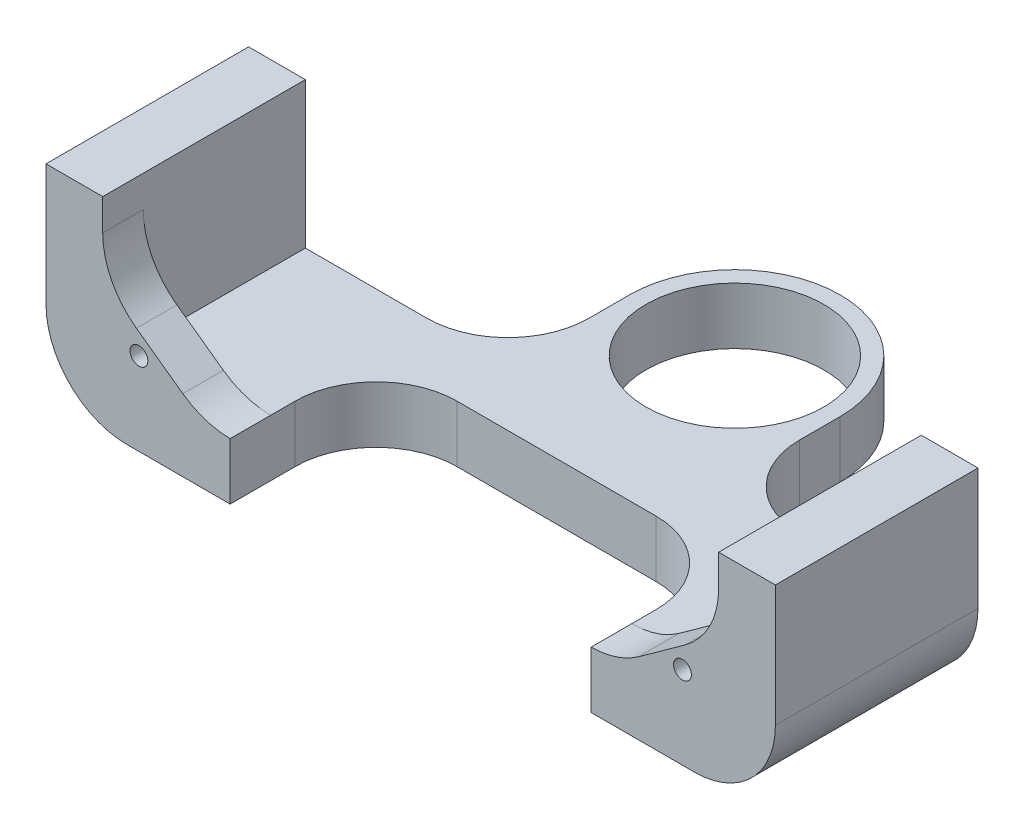
SolidWorks part; units mm, degrees
material "PVC 0.007 Plasticized"
ref_plane "Front Plane" through (0, 0, 0) normal (0, 0, 1) x (1, 0, 0)
ref_plane "Top Plane" through (0, 0, 0) normal (0, 1, 0) x (1, 0, 0)
ref_plane "Right Plane" through (0, 0, 0) normal (1, 0, 0) x (0, 0, -1)
sketch "Sketch1" plane through (0, 0, 0) normal (0, 1, 0) x (1, 0, 0)
  line L2 (0, 0) -> (0, -40)
  line L3 (0, -40) -> (26, -40)
  line L4 (26, 0) -> (26, -40)
  arc A0 (26, 0) -> (0, 0) centre (13, 0) ccw
  circle A1 centre (13, 0) radius 10.975
  dimension "D3" = 21.95
  dimension "D1" = 40
  dimension "D2" = 26
extrude "Boss-Extrude1" add sketch "Sketch1" along normal blind 7
sketch "Sketch2" plane through (0, 0, 40) normal (0, 0, 1) x (1, 0, 0)
  line L0 (26, 0) -> (58, 0)
  line L1 (58, 0) -> (58, 25)
  line L2 (58, 25) -> (51, 25)
  line L3 (51, 25) -> (51, 7) construction
  line L4 (51, 7) -> (26, 7) construction
  line L5 (26, 7) -> (26, 0) construction
  line L6 (0, 0) -> (26, 0) construction
  line L7 (51, 16) -> (38.5, 7)
  line L8 (38.5, 7) -> (26, 7)
  line L9 (51, 16) -> (51, 25)
  line L10 (44.75, 11.5) -> (51, 7) construction
  circle A0 centre (46.5354, 10.2145) radius 1.1
  point P13 (13, 0)
  point P20 (46.6726, 10.1158)
  line M8 (26, 0) -> (26, 7)
  dimension "D3" = 2.2
  dimension "D1" = 45
  dimension "D2" = 25
  dimension "D4" = 2.2
extrude "Boss-Extrude2" add sketch "Sketch2" against normal blind 5 contours L9 L7 L8 L0 L1 L2 A0 M8
sketch "Sketch3" plane through (0, 0, 35) normal (0, 0, -1) x (-1, 0, 0)
  line L0 (-51, 16) -> (-51, 7)
  line L1 (-51, 7) -> (-38.5, 7)
  line L7 (-51, 16) -> (-51, 25)
  line L8 (-51, 25) -> (-58, 25)
  line L9 (-58, 25) -> (-58, 0)
  line L10 (-58, 0) -> (-26, 0)
  line L11 (-26, 0) -> (-26, 7)
  line L12 (-26, 7) -> (-38.5, 7)
  line L13 (-38.5, 7) -> (-51, 16)
  line L14 (-51, 16) -> (-51, 25)
  line L15 (-51, 25) -> (-58, 25)
  line L16 (-58, 25) -> (-58, 0)
  line L17 (-58, 0) -> (-26, 0)
  line L18 (-26, 0) -> (-26, 7)
  line L19 (-26, 7) -> (-38.5, 7)
  dimension "D1" = 0
extrude "Boss-Extrude3" add sketch "Sketch3" along normal blind 20
ref_plane "Plane1" through (13, 0, 0) normal (1, 0, 0) x (0, 0, -1)
mirror "Mirror1" about plane through (13, 0, 0) normal (1, 0, 0) of "Boss-Extrude3", "Boss-Extrude2"
fillet "Fillet1" radius 10 8 edges at (51, 16, 37.5) (58, 0, 27.5) (38.5, 7, 37.5) (26, 3.5, 15) (-25, 16, 37.5) (-12.5, 7, 37.5) (-32, 0, 27.5) (0, 3.5, 15)
sketch "Sketch5" plane through (0, 7, 0) normal (0, 1, 0) x (1, 0, 0)
  line L0 (-9.2745, -35) -> (-9.2745, -40) construction
  line L1 (-9.2745, -22) -> (35.2745, -22)
  line L2 (-9.2745, -22) -> (-9.2745, -40)
  line L3 (-9.2745, -40) -> (35.2745, -40)
  line L4 (35.2745, -22) -> (35.2745, -40)
  dimension "D1" = 18
extrude "Cut-Extrude2" cut sketch "Sketch5" against normal up to surface (7 mm away) up to face at (13, 0, 14.1142)
fillet "Fillet2" radius 10 2 edges at (35.2745, 3.5, 22) (-9.2745, 3.5, 22)
